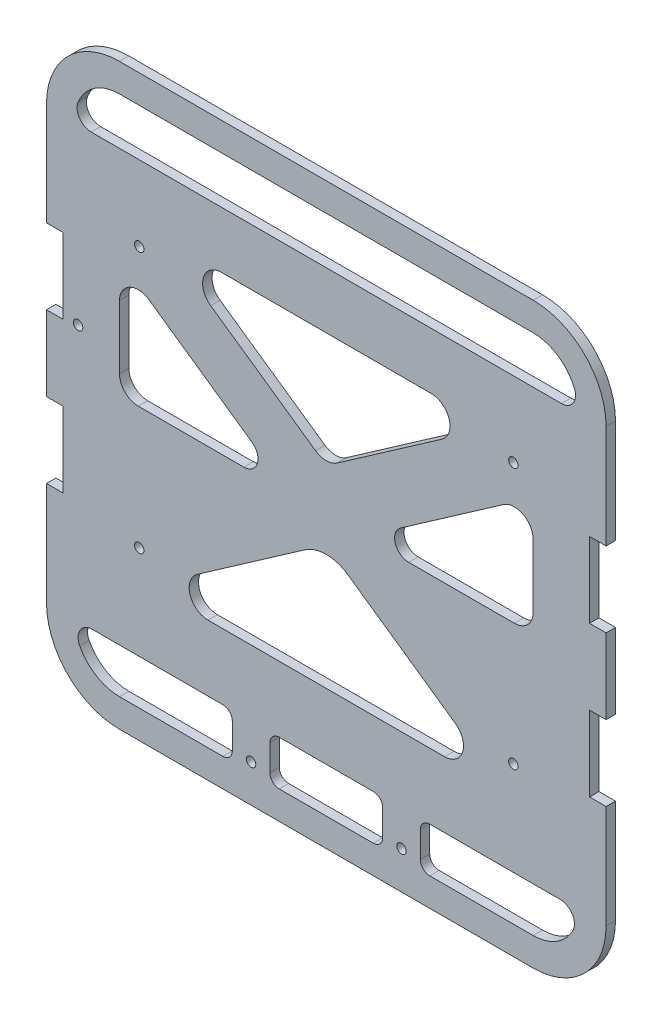
SolidWorks part; units mm, degrees
ref_plane "Front Plane" through (0, 0, 0) normal (0, 0, 1) x (1, 0, 0)
ref_plane "Top Plane" through (0, 0, 0) normal (0, 1, 0) x (1, 0, 0)
ref_plane "Right Plane" through (0, 0, 0) normal (1, 0, 0) x (0, 0, -1)
ref_plane "Plane1" through (0, 0, -676.275) normal (0, 0, 1) x (1, 0, 0)
sketch "Sketch1" plane through (0, 0, -676.275) normal (0, 0, 1) x (1, 0, 0)
  line L0 (94.488, -171.45) -> (94.488, -136.525)
  line L1 (94.488, -136.525) -> (88.9, -136.525)
  line L2 (88.9, -136.525) -> (88.9, -111.125)
  line L3 (88.9, -111.125) -> (94.488, -111.125)
  line L4 (94.488, -111.125) -> (94.488, -85.725)
  line L5 (94.488, -85.725) -> (88.9, -85.725)
  line L6 (88.9, -85.725) -> (88.9, -60.325)
  line L7 (88.9, -60.325) -> (94.488, -60.325)
  line L8 (94.488, -60.325) -> (94.488, -25.4)
  line L9 (69.85, -0.762) -> (-69.85, -0.762)
  line L10 (-94.488, -25.4) -> (-94.488, -60.325)
  line L11 (-94.488, -60.325) -> (-88.9, -60.325)
  line L12 (-88.9, -60.325) -> (-88.9, -85.725)
  line L13 (-88.9, -85.725) -> (-94.488, -85.725)
  line L14 (-94.488, -85.725) -> (-94.488, -111.125)
  line L15 (-94.488, -111.125) -> (-88.9, -111.125)
  line L16 (-88.9, -111.125) -> (-88.9, -136.525)
  line L17 (-88.9, -136.525) -> (-94.488, -136.525)
  line L18 (-94.488, -136.525) -> (-94.488, -171.45)
  line L19 (-69.85, -196.088) -> (69.85, -196.088)
  line L20 (7.2646, -112.3283) -> (43.598, -137.6665)
  line L21 (39.9657, -149.225) -> (-39.9657, -149.225)
  line L22 (-43.598, -137.6665) -> (-7.2646, -112.3283)
  line L23 (39.0453, -56.8078) -> (3.6323, -81.5041)
  line L24 (-3.6323, -81.5041) -> (-39.0453, -56.8078)
  line L25 (-35.4129, -45.2493) -> (35.4129, -45.2493)
  line L26 (69.85, -70.7201) -> (69.85, -92.075)
  line L27 (63.5, -98.425) -> (27.8268, -98.425)
  line L28 (25.1025, -89.7561) -> (59.8677, -65.5116)
  line L29 (-59.8677, -65.5116) -> (-25.1025, -89.7561)
  line L30 (-27.8268, -98.425) -> (-63.5, -98.425)
  line L31 (-69.85, -92.075) -> (-69.85, -70.7201)
  line L32 (0, -0.762) -> (0, -196.088) construction
  line L33 (-63.1655, -51.5993) -> (63.1655, -51.5993) construction
  line L34 (-63.1655, -51.5993) -> (-63.1655, -139.7) construction
  line L35 (-63.1655, -139.7) -> (63.1655, -139.7) construction
  line L36 (63.1655, -51.5993) -> (63.1655, -139.7) construction
  line L37 (-63.1655, -51.5993) -> (63.1655, -139.7) construction
  line L38 (-63.1655, -139.7) -> (63.1655, -51.5993) construction
  line L39 (-69.85, -186.563) -> (-34.925, -186.563)
  line L40 (-79.0397, -171.45) -> (-34.925, -171.45)
  line L41 (-25.4, -183.388) -> (25.4, -183.388) construction
  line L42 (69.85, -10.287) -> (-69.85, -10.287)
  line L43 (-31.75, -174.625) -> (-31.75, -183.388)
  line L44 (-19.05, -183.388) -> (-19.05, -174.625)
  line L45 (19.05, -174.625) -> (19.05, -183.388)
  line L46 (31.75, -174.625) -> (31.75, -183.388)
  line L47 (-15.875, -171.45) -> (15.875, -171.45)
  line L48 (34.925, -171.45) -> (79.0397, -171.45)
  line L49 (-15.875, -186.563) -> (15.875, -186.563)
  line L50 (-69.85, -186.563) -> (69.85, -186.563) construction
  line L51 (34.925, -186.563) -> (69.85, -186.563)
  line L52 (-79.4117, -26.1993) -> (79.4117, -26.1993)
  circle A0 centre (63.1655, -139.7) radius 1.5875
  circle A1 centre (-83.82, -84.8367) radius 1.5875
  circle A2 centre (-63.1655, -51.5993) radius 1.5875
  circle A3 centre (25.4, -183.388) radius 1.5875
  arc A4 (69.85, -196.088) -> (94.488, -171.45) centre (69.85, -171.45) ccw
  arc A5 (94.488, -25.4) -> (69.85, -0.762) centre (69.85, -25.4) ccw
  arc A6 (-69.85, -0.762) -> (-94.488, -25.4) centre (-69.85, -25.4) ccw
  arc A7 (-94.488, -171.45) -> (-69.85, -196.088) centre (-69.85, -171.45) ccw
  circle A8 centre (-25.4, -183.388) radius 1.5875
  arc A9 (43.598, -137.6665) -> (39.9657, -149.225) centre (39.9657, -142.875) cw
  arc A10 (-39.9657, -149.225) -> (-43.598, -137.6665) centre (-39.9657, -142.875) cw
  arc A11 (-7.2646, -112.3283) -> (7.2646, -112.3283) centre (0, -122.7454) cw
  circle A12 centre (-63.1655, -139.7) radius 1.5875
  arc A13 (3.6323, -81.5041) -> (-3.6323, -81.5041) centre (0, -76.2956) cw
  arc A14 (-35.4129, -45.2493) -> (-39.0453, -56.8078) centre (-35.4129, -51.5993) ccw
  arc A15 (35.4129, -45.2493) -> (39.0453, -56.8078) centre (35.4129, -51.5993) cw
  arc A16 (69.85, -92.075) -> (63.5, -98.425) centre (63.5, -92.075) cw
  arc A17 (27.8268, -98.425) -> (25.1025, -89.7561) centre (27.8268, -93.6625) cw
  arc A18 (59.8677, -65.5116) -> (69.85, -70.7201) centre (63.5, -70.7201) cw
  arc A19 (-25.1025, -89.7561) -> (-27.8268, -98.425) centre (-27.8268, -93.6625) cw
  arc A20 (-63.5, -98.425) -> (-69.85, -92.075) centre (-63.5, -92.075) cw
  arc A21 (-69.85, -70.7201) -> (-59.8677, -65.5116) centre (-63.5, -70.7201) cw
  circle A22 centre (63.1655, -51.5993) radius 1.5875
  circle A23 centre (-63.1655, -51.5993) radius 12.7 construction
  arc A24 (-83.2682, -178.4038) -> (-69.85, -186.563) centre (-69.85, -171.45) ccw
  arc A25 (69.85, -186.563) -> (83.2682, -178.4038) centre (69.85, -171.45) ccw
  arc A26 (-84.963, -171.45) -> (-69.85, -186.563) centre (-69.85, -171.45) ccw construction
  arc A27 (-83.2682, -178.4038) -> (-79.0397, -171.45) centre (-79.0397, -176.2125) cw
  arc A28 (69.85, -186.563) -> (84.963, -171.45) centre (69.85, -171.45) ccw construction
  arc A29 (83.2682, -178.4038) -> (79.0397, -171.45) centre (79.0397, -176.2125) ccw
  arc A30 (-31.75, -183.388) -> (-34.925, -186.563) centre (-34.925, -183.388) cw
  arc A31 (-19.05, -183.388) -> (-15.875, -186.563) centre (-15.875, -183.388) ccw
  arc A32 (83.8112, -19.6132) -> (69.85, -10.287) centre (69.85, -25.4) ccw
  arc A33 (-69.85, -10.287) -> (-83.8112, -19.6132) centre (-69.85, -25.4) ccw
  arc A34 (19.05, -183.388) -> (15.875, -186.563) centre (15.875, -183.388) cw
  arc A35 (31.75, -183.388) -> (34.925, -186.563) centre (34.925, -183.388) ccw
  arc A36 (31.75, -174.625) -> (34.925, -171.45) centre (34.925, -174.625) cw
  arc A37 (19.05, -174.625) -> (15.875, -171.45) centre (15.875, -174.625) ccw
  arc A38 (-19.05, -174.625) -> (-15.875, -171.45) centre (-15.875, -174.625) cw
  arc A39 (-31.75, -174.625) -> (-34.925, -171.45) centre (-34.925, -174.625) ccw
  arc A40 (-79.4117, -26.1993) -> (-83.8112, -19.6132) centre (-79.4117, -21.4368) cw
  arc A41 (79.4117, -26.1993) -> (83.8112, -19.6132) centre (79.4117, -21.4368) ccw
  arc A43 (-69.85, -10.287) -> (-84.963, -25.4) centre (-69.85, -25.4) ccw construction
  arc A44 (84.963, -25.4) -> (69.85, -10.287) centre (69.85, -25.4) ccw construction
  point P80 (0, -51.5993)
  point P96 (0, -183.388)
  dimension "D2" = 3.175
  dimension "D13" = 25.4
  dimension "D16" = 4.7625
  dimension "D24" = 3.175
  dimension "D25" = 3.175
  dimension "D26" = 3.175
  dimension "D27" = 25.4
  dimension "D28" = 6.35
  dimension "D29" = 4.7625
  dimension "D30" = 6.35
  dimension "D31" = 6.35
  dimension "D32" = 12.7
  dimension "D1" = 126.331
  dimension "D3" = 31.75
  dimension "D4" = 12.7
  dimension "D5" = 9.525
  dimension "D6" = 9.525
  dimension "D7" = 88.1007
  dimension "D8" = 9.525
  dimension "D9" = 9.525
  dimension "D10" = 19.05
  dimension "D11" = 19.05
  dimension "D12" = 6.35
  dimension "D14" = 22.225
  dimension "D17" = 12.7
  dimension "D18" = 50.8
  dimension "D20" = 12.7
  dimension "D21" = 12.7
  dimension "D22" = 6.35
  dimension "D23" = 6.35
  dimension "D15" = 9.525
  dimension "D19" = 9.525
extrude "Boss-Extrude1" add sketch "Sketch1" against normal blind 3.175
